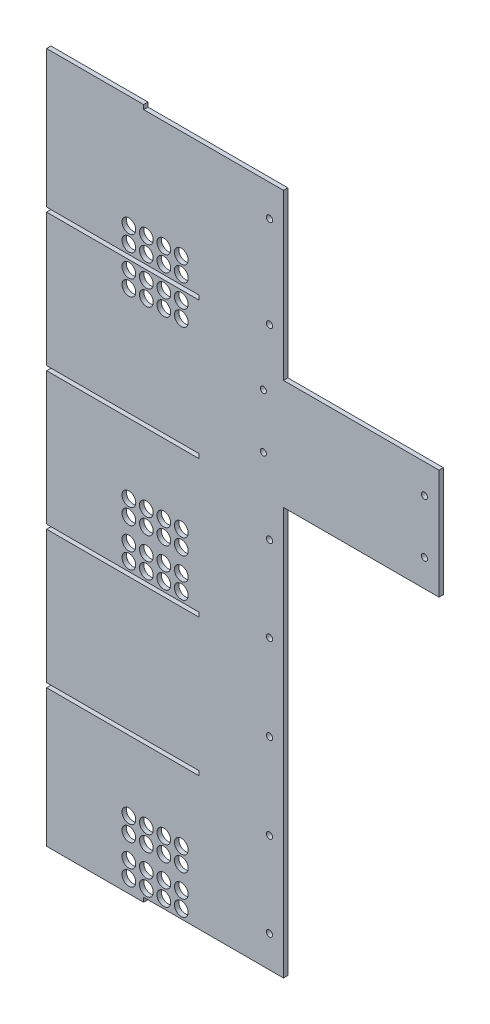
SolidWorks part; units mm, degrees
material "6061-T6 (SS)"
ref_plane "X-Y Datum" through (0, 0, 0) normal (0, 0, 1) x (1, 0, 0)
ref_plane "X-Z Datum" through (0, 0, 0) normal (0, 1, 0) x (1, 0, 0)
ref_plane "Y-Z Datum" through (0, 0, 0) normal (1, 0, 0) x (0, 0, -1)
sketch "Sketch1" plane through (0, 0, 0) normal (0, 0, 1) x (1, 0, 0)
  line L1 (129.0131, 254.2454) -> (-18.6854, 254.2454)
  line L3 (129.0131, -241.3467) -> (-18.6854, -241.3467)
  line L4 (-18.6854, 254.2454) -> (-18.6854, 157.667)
  line L24 (129.0131, 254.2454) -> (129.0131, -241.3467)
  line L25 (92.0885, 157.667) -> (-18.6854, 157.667)
  line L27 (92.0885, 154.492) -> (-18.6854, 154.492)
  line L29 (92.0885, 57.9136) -> (-18.6854, 57.9136)
  line L31 (92.0885, 54.7386) -> (-18.6854, 54.7386)
  line L33 (92.0885, -41.8399) -> (-18.6854, -41.8399)
  line L35 (92.0885, -45.0149) -> (-18.6854, -45.0149)
  line L37 (92.0885, -141.5933) -> (-18.6854, -141.5933)
  line L39 (92.0885, -144.7683) -> (-18.6854, -144.7683)
  line L41 (92.0885, -141.5933) -> (92.0885, -144.7683)
  line L42 (92.0885, -41.8399) -> (92.0885, -45.0149)
  line L43 (92.0885, 57.9136) -> (92.0885, 54.7386)
  line L44 (-18.6854, -144.7683) -> (-18.6854, -241.3467)
  line L45 (-18.6854, -45.0149) -> (-18.6854, -141.5933)
  line L46 (-18.6854, 54.7386) -> (-18.6854, -41.8399)
  line L47 (-18.6854, 154.492) -> (-18.6854, 57.9136)
  line L48 (92.0885, 157.667) -> (92.0885, 154.492)
extrude "Boss-Extrude2" add sketch "Sketch1" along normal blind 3.175
sketch "Sketch4" plane through (0, 0, 3.175) normal (0, 0, 1) x (1, 0, 0)
  line L0 (129.0131, 254.2454) -> (153.4072, 240.1614) construction
  line L2 (129.0131, 254.2454) -> (129.0131, -241.3467)
  line L4 (153.4072, 240.1614) -> (153.4072, -227.2627)
  line L6 (153.4072, -227.2627) -> (153.4072, -241.3467)
  line L7 (153.4072, -241.3467) -> (129.0131, -241.3467)
  line L8 (129.0131, 254.2454) -> (153.4072, 254.2454)
  line L9 (153.4072, 254.2454) -> (153.4072, 240.1614)
extrude "Boss-Extrude3" add sketch "Sketch4" against normal through all
sketch "Sketch7" plane through (0, 0, 3.175) normal (0, 0, 1) x (1, 0, 0)
  line L0 (51.8072, -241.3467) -> (-18.6854, -241.3467)
  line L1 (51.8072, -244.5217) -> (51.8072, -241.3467)
  line L2 (153.4072, -244.5217) -> (51.8072, -244.5217)
  line L3 (153.4072, -244.5217) -> (153.4072, -257.2217)
  line L4 (153.4072, -257.2217) -> (30.4963, -257.2217)
  line L5 (30.4963, -257.2217) -> (6.7146, -273.4777)
  line L6 (-18.6854, -273.4777) -> (6.7146, -273.4777)
  line L7 (-18.6854, -241.3467) -> (-18.6854, -273.4777)
  point P0 (-51.634, -260.9767)
  point P9 (-18.6854, -241.3467)
extrude "Boss-Extrude6" [suppressed] add sketch "Sketch7" against normal through all
sketch "Sketch8" [suppressed] plane through (0, 0, 3.175) normal (0, 0, 1) x (1, 0, 0)
  line L1 (153.4072, -257.2217) -> (221.7231, -257.2217)
  line L2 (153.4072, -257.2217) -> (153.4072, -244.5217)
  line L3 (153.4072, -244.5217) -> (221.7231, -244.5217)
  line L4 (221.7231, -257.2217) -> (221.7231, -244.5217)
  line L5 (153.4072, -241.3467) -> (221.7231, -241.3467)
  line L6 (153.4072, -241.3467) -> (153.4072, -144.7683)
  line L7 (153.4072, -144.7683) -> (221.7231, -144.7683)
  line L8 (221.7231, -241.3467) -> (221.7231, -144.7683)
  dimension "D1" = 68.3158
extrude "Boss-Extrude7" [suppressed] add sketch "Sketch8" against normal through all
sketch "Sketch11" plane through (0, 0, 3.175) normal (0, 0, 1) x (1, 0, 0)
  line L0 (92.0885, 54.7386) -> (153.4072, 54.7386) construction
  line L1 (153.4072, 134.68) -> (266.4372, 134.68)
  line L2 (153.4072, -241.3467) -> (153.4072, 254.2454) construction
  line L3 (266.4372, 134.68) -> (266.4372, 54.7386)
  line L4 (266.4372, 54.7386) -> (153.4072, 54.7386)
  line L5 (153.4072, 54.7386) -> (153.4072, 134.68)
  line L6 (153.4072, -241.3467) -> (153.4072, 254.2454) construction
extrude "Boss-Extrude8" add sketch "Sketch11" against normal through all
sketch "Sketch12" plane through (0, 0, 0) normal (0, 0, -1) x (-1, 0, 0)
  line L1 (18.6854, 254.2454) -> (-51.8072, 254.2454)
  line L2 (18.6854, 254.2454) -> (18.6854, 257.4204)
  line L3 (18.6854, 257.4204) -> (-51.8072, 257.4204)
  line L4 (-51.8072, 254.2454) -> (-51.8072, 257.4204)
  line L5 (18.6854, -241.3467) -> (-51.8072, -241.3467)
  line L6 (18.6854, -241.3467) -> (18.6854, -244.5217)
  line L7 (18.6854, -244.5217) -> (-51.8072, -244.5217)
  line L8 (-51.8072, -241.3467) -> (-51.8072, -244.5217)
extrude "Boss-Extrude9" add sketch "Sketch12" against normal through all
sketch "Sketch14" plane through (0, 0, 3.175) normal (0, 0, 1) x (1, 0, 0)
  line L0 (-18.6854, -244.5217) -> (269.694, -244.5217)
  line L1 (-18.6854, -244.5217) -> (-18.6854, 277.9004)
  line L2 (-18.6854, 277.9004) -> (269.694, 277.9004)
  line L3 (269.694, -244.5217) -> (269.694, 277.9004)
  point P0 (143.2472, -231.1146)
  point P1 (143.2472, -158.2226)
  point P2 (143.2472, -85.3305)
  point P3 (143.2472, -12.4385)
  point P4 (143.2472, 60.4536)
  point P5 (170.6792, 87.8856)
  point P6 (210.7117, 87.8856)
  point P7 (250.7441, 87.8856)
  point P8 (256.2772, 93.4187)
  point P9 (256.2772, 119.6462)
  point P10 (256.2772, 145.8738)
  point P11 (143.2472, 173.5725)
  point P12 (143.2472, 208.7929)
  point P13 (143.2472, 244.0133)
sketch "Sketch15" plane through (0, 0, 3.175) normal (0, 0, 1) x (1, 0, 0)
  line L0 (-18.6854, 257.4204) -> (23.3644, 257.4204) construction
  line L1 (-18.6854, 257.4204) -> (-18.6854, 239.7041) construction
  line L2 (-18.6854, 239.7041) -> (23.3644, 239.7041) construction
  line L3 (23.3644, 257.4204) -> (23.3644, 239.7041) construction
  line L4 (258.5632, 130.1671) -> (255.7997, 130.1671) construction
  line L5 (255.7997, 130.1671) -> (255.7997, 113.344) construction
  circle A0 centre (143.2472, 231.3133) radius 2.25
  circle A1 centre (143.2472, 164.652) radius 2.25
  circle A2 centre (255.7997, 113.344) radius 2.25
  circle A3 centre (255.7997, 74.4957) radius 2.25
  circle A4 centre (143.2472, 29.3386) radius 2.25
  circle A5 centre (143.2472, -32.3342) radius 2.25
  circle A6 centre (143.2472, -94.538) radius 2.25
  circle A7 centre (143.2472, -156.7418) radius 2.25
  circle A8 centre (143.2472, -218.4146) radius 2.25
  point P0 (143.2472, 231.3133)
  point P1 (143.2472, 164.652)
  point P2 (255.7997, 113.344)
  point P3 (255.7997, 74.4957)
  point P4 (143.2472, 29.3386)
  point P5 (143.2472, -32.3342)
  point P6 (143.2472, -94.538)
  point P7 (143.2472, -156.7418)
  point P8 (143.2472, -218.4146)
  point P13 (-18.6854, 257.4204)
  point P35 (255.7997, 74.4957)
extrude "Cut-Extrude1" cut sketch "Sketch15" against normal through all
sketch "Sketch16" plane through (0, 0, 3.175) normal (0, 0, 1) x (1, 0, 0)
  line L0 (141.8421, 121.4512) -> (135.7421, 121.4512) construction
  line L1 (141.8421, 82.1409) -> (135.7421, 82.1409) construction
  line L2 (266.4372, 134.68) -> (206.1233, 134.68) construction
  line L3 (266.4372, 134.68) -> (266.4372, 101.236) construction
  line L4 (266.4372, 101.236) -> (206.1233, 101.236) construction
  line L5 (206.1233, 134.68) -> (206.1233, 101.236) construction
  circle A0 centre (138.7921, 121.4512) radius 2.25
  circle A1 centre (138.7921, 82.1409) radius 2.25
  point P12 (266.4372, 134.68)
extrude "Cut-Extrude2" cut sketch "Sketch16" against normal through all
sketch "Sketch17" plane through (0, 0, 3.175) normal (0, 0, 1) x (1, 0, 0)
  line L0 (92.0885, 84.121) -> (84.4685, 84.121) construction
  line L1 (92.0885, -215.1393) -> (84.4685, -215.1393) construction
  line L2 (92.0885, -15.6324) -> (84.4685, -15.6324) construction
  line L3 (84.4685, -190.1393) -> (34.4685, -190.1393) construction
  line L4 (84.4685, -190.1393) -> (84.4685, -240.1393) construction
  line L5 (84.4685, -240.1393) -> (34.4685, -240.1393) construction
  line L6 (34.4685, -190.1393) -> (34.4685, -240.1393) construction
  line L7 (92.0885, -215.1393) -> (84.4685, -215.1393) construction
  line L8 (34.4685, 9.3676) -> (84.4685, 9.3676) construction
  line L9 (34.4685, 9.3676) -> (34.4685, -40.6324) construction
  line L10 (34.4685, -40.6324) -> (84.4685, -40.6324) construction
  line L11 (84.4685, 9.3676) -> (84.4685, -40.6324) construction
  line L12 (34.4685, -190.1393) -> (84.4685, -190.1393) construction
  line L13 (34.4685, -190.1393) -> (34.4685, -240.1393) construction
  line L14 (34.4685, -240.1393) -> (84.4685, -240.1393) construction
  line L15 (84.4685, -190.1393) -> (84.4685, -240.1393) construction
  line L16 (92.0885, 156.0795) -> (84.4685, 156.0795) construction
  line L17 (34.4685, 181.0795) -> (84.4685, 181.0795) construction
  line L18 (34.4685, 181.0795) -> (34.4685, 131.0795) construction
  line L19 (34.4685, 131.0795) -> (84.4685, 131.0795) construction
  line L20 (84.4685, 181.0795) -> (84.4685, 131.0795) construction
  circle A0 centre (79.1915, 4.0169) radius 5
  circle A1 centre (66.4915, 4.0169) radius 5
  circle A2 centre (53.7915, 4.0169) radius 5
  circle A3 centre (41.0915, 4.0169) radius 5
  circle A4 centre (66.4915, -7.4131) radius 5
  circle A5 centre (53.7915, -7.4131) radius 5
  circle A6 centre (41.0915, -7.4131) radius 5
  circle A7 centre (79.1915, -7.4131) radius 5
  circle A8 centre (41.0915, -35.2818) radius 5
  circle A9 centre (41.0915, -23.8518) radius 5
  circle A10 centre (53.7915, -35.2818) radius 5
  circle A11 centre (53.7915, -23.8518) radius 5
  circle A12 centre (66.4915, -35.2818) radius 5
  circle A13 centre (66.4915, -23.8518) radius 5
  circle A14 centre (79.1915, -23.8518) radius 5
  circle A15 centre (79.1915, -35.2818) radius 5
  circle A16 centre (79.1915, -195.4899) radius 5
  circle A17 centre (66.4915, -195.4899) radius 5
  circle A18 centre (53.7915, -195.4899) radius 5
  circle A19 centre (41.0915, -195.4899) radius 5
  circle A20 centre (66.4915, -206.9199) radius 5
  circle A21 centre (53.7915, -206.9199) radius 5
  circle A22 centre (41.0915, -206.9199) radius 5
  circle A23 centre (79.1915, -206.9199) radius 5
  circle A24 centre (41.0915, -234.7886) radius 5
  circle A25 centre (41.0915, -223.3586) radius 5
  circle A26 centre (53.7915, -234.7886) radius 5
  circle A27 centre (53.7915, -223.3586) radius 5
  circle A28 centre (66.4915, -234.7886) radius 5
  circle A29 centre (66.4915, -223.3586) radius 5
  circle A30 centre (79.1915, -223.3586) radius 5
  circle A31 centre (79.1915, -234.7886) radius 5
  circle A32 centre (79.1915, 175.7289) radius 5
  circle A33 centre (66.4915, 175.7289) radius 5
  circle A34 centre (53.7915, 175.7289) radius 5
  circle A35 centre (41.0915, 175.7289) radius 5
  circle A36 centre (66.4915, 164.2989) radius 5
  circle A37 centre (53.7915, 164.2989) radius 5
  circle A38 centre (41.0915, 164.2989) radius 5
  circle A39 centre (79.1915, 164.2989) radius 5
  circle A40 centre (41.0915, 136.4301) radius 5
  circle A41 centre (41.0915, 147.8601) radius 5
  circle A42 centre (53.7915, 136.4301) radius 5
  circle A43 centre (53.7915, 147.8601) radius 5
  circle A44 centre (66.4915, 136.4301) radius 5
  circle A45 centre (66.4915, 147.8601) radius 5
  circle A46 centre (79.1915, 147.8601) radius 5
  circle A47 centre (79.1915, 136.4301) radius 5
extrude "Cut-Extrude3" cut sketch "Sketch17" against normal through all
